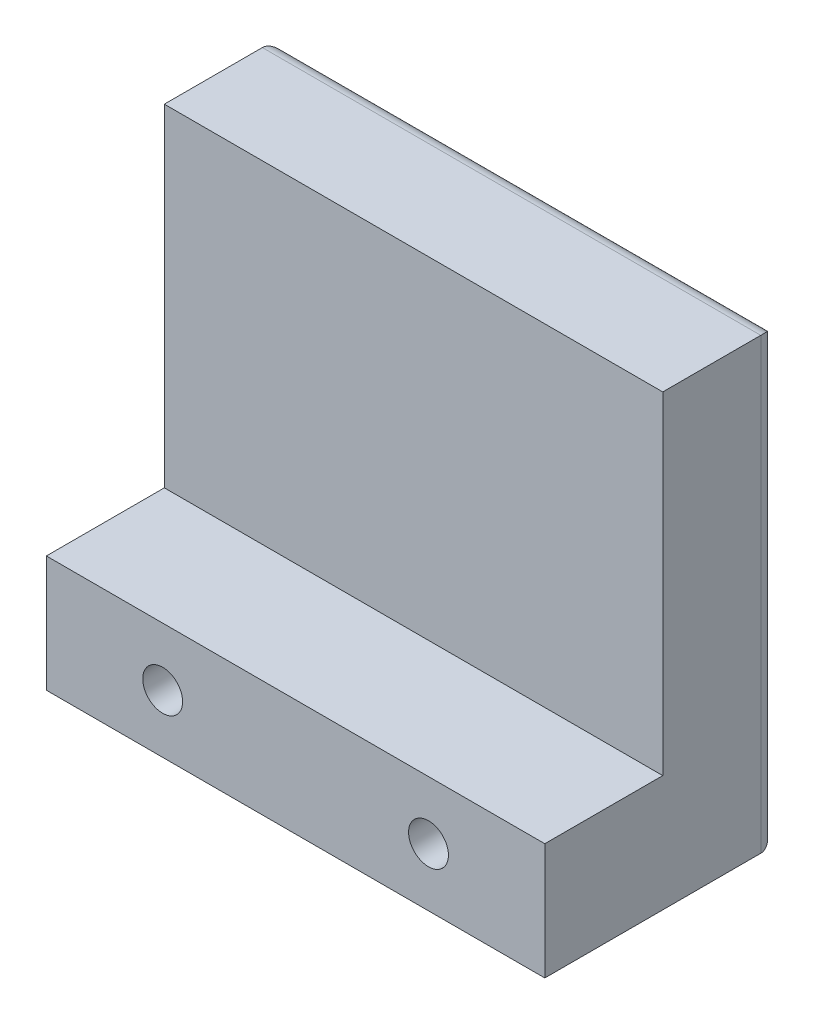
SolidWorks part; units mm, degrees
ref_plane "Front Plane" through (0, 0, 0) normal (0, 0, 1) x (1, 0, 0)
ref_plane "Top Plane" through (0, 0, 0) normal (0, 1, 0) x (1, 0, 0)
ref_plane "Right Plane" through (0, 0, 0) normal (1, 0, 0) x (0, 0, -1)
sketch "Sketch2" plane through (0, 0, 0) normal (0, 1, 0) x (1, 0, 0)
  line L1 (19.05, -8.89) -> (-19.05, -8.89)
  line L2 (19.05, -8.89) -> (19.05, 8.89)
  line L3 (19.05, 8.89) -> (-19.05, 8.89)
  line L4 (-19.05, -8.89) -> (-19.05, 8.89)
  line L5 (19.05, -8.89) -> (-19.05, 8.89) construction
  line L6 (19.05, 8.89) -> (-19.05, -8.89) construction
  point P0 (0, 0)
  dimension "D1" = 17.78
  dimension "D2" = 38.1
extrude "Boss-Extrude1" add sketch "Sketch2" along normal blind 8.89
sketch "Sketch3" plane through (0, 8.89, 0) normal (0, 1, 0) x (1, 0, 0)
  line L0 (19.05, -8.89) -> (19.05, 8.89) construction
  line L1 (-19.05, 8.89) -> (19.05, 8.89)
  line L2 (-19.05, 8.89) -> (-19.05, 0.127)
  line L3 (-19.05, 0.127) -> (19.05, 0.127)
  line L4 (19.05, 8.89) -> (19.05, 0.127)
  line L5 (-19.05, 0.127) -> (-19.05, -8.89) construction
  dimension "D1" = 9.017
extrude "Boss-Extrude2" add sketch "Sketch3" along normal blind 25.4
sketch "Sketch4" plane through (0, 0, 8.89) normal (0, 0, 1) x (1, 0, 0)
  line L0 (-10.16, 4.445) -> (10.16, 4.445) construction
  line L1 (0, 4.445) -> (0, 8.89) construction
  line L2 (-19.05, 8.89) -> (19.05, 8.89) construction
  line L3 (-10.16, 4.445) -> (-19.05, 4.445) construction
  line L4 (-19.05, 8.89) -> (-19.05, 0) construction
  circle A0 centre (-10.16, 4.445) radius 1.524
  circle A1 centre (10.16, 4.445) radius 1.524
  dimension "D1" = 3.048
  dimension "D2" = 20.32
extrude "Cut-Extrude1" cut sketch "Sketch4" against normal through all
fillet "Fillet1" radius 1.27 4 edges at (0, 0, -8.89) (-19.05, 17.145, -8.89) (0, 34.29, -8.89) (19.05, 17.145, -8.89)
